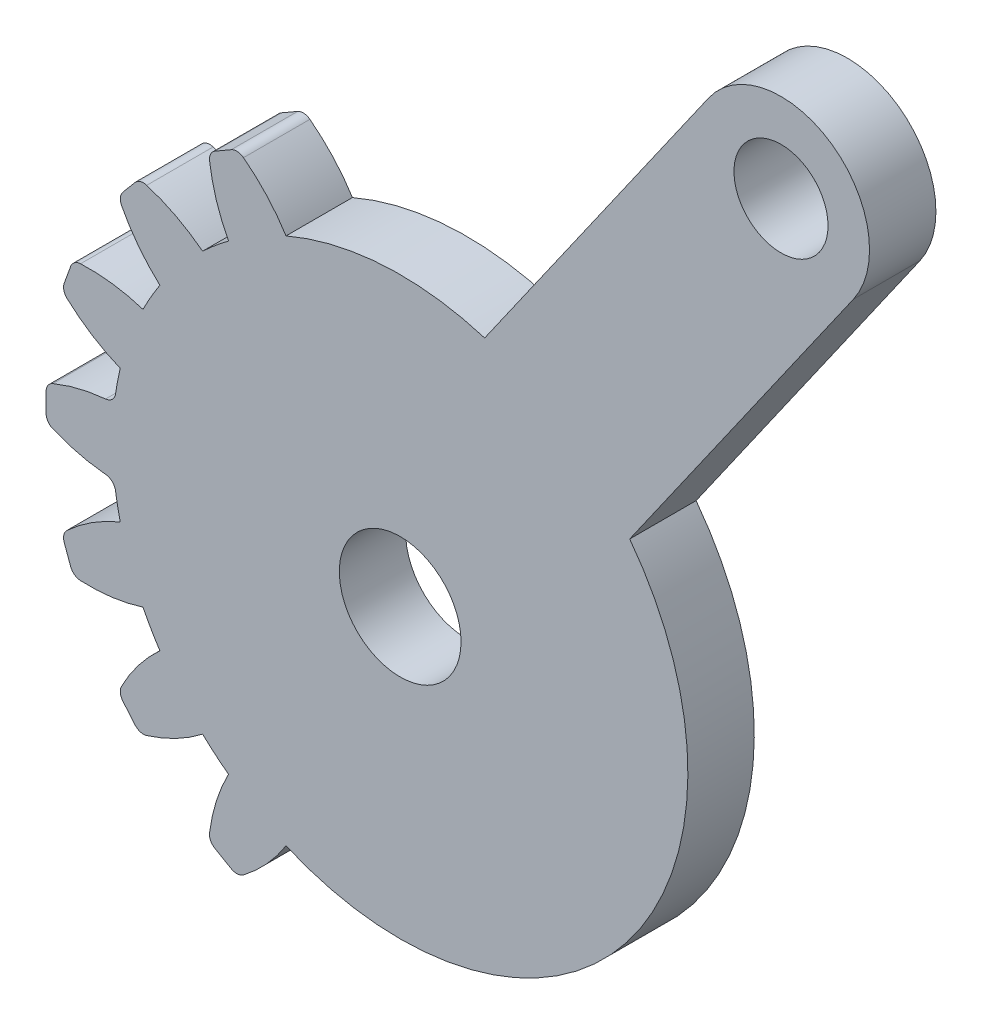
SolidWorks part; units mm, degrees
material "ABS"
ref_plane "Front Plane" through (0, 0, 0) normal (0, 0, 1) x (1, 0, 0)
ref_plane "Top Plane" through (0, 0, 0) normal (0, 1, 0) x (1, 0, 0)
ref_plane "Right Plane" through (0, 0, 0) normal (1, 0, 0) x (0, 0, -1)
sketch "Sketch1" plane through (0, 0, 0) normal (0, 0, 1) x (1, 0, 0)
  circle A1 centre (43.95, -5.65) radius 2.75
  circle A2 centre (43.95, -5.65) radius 13
  dimension "D1" = 26
  dimension "D2" = 5.5
extrude "Boss-Extrude1" add sketch "Sketch1" along normal blind 3 contours A2
sketch "Sketch2" plane through (0, 0, 3) normal (0, 0, 1) x (1, 0, 0)
  line L0 (43.95, -5.65) -> (-22.5318, -5.65) construction
  line L1 (27.95, -4.9) -> (27.95, -6.4)
  arc A0 (27.95, -6.4) -> (31.0368, -7.15) centre (31.3446, 0.8441) ccw
  arc A1 (31.0368, -4.15) -> (31.0368, -7.15) centre (43.95, -5.65) ccw
  circle A2 centre (43.95, -5.65) radius 13 construction
  arc A3 (27.95, -4.9) -> (31.0368, -4.15) centre (31.3446, -12.1441) cw
  point P10 (27.95, -5.65)
  dimension "D3" = 8
  dimension "D1" = 0.75
  dimension "D2" = 1.5
  dimension "D4" = 16
extrude "Boss-Extrude2" add sketch "Sketch2" against normal blind 3
fillet "Fillet1" radius 0.5 4 edges at (31.0368, -7.15, 1.5) (27.95, -6.4, 1.5) (27.95, -4.9, 1.5) (31.0368, -4.15, 1.5)
pattern_circular "CirPattern1" count 4 over 60 about axis through (43.95, -5.65, 0) along (0, 0, 1) of "Boss-Extrude2"
pattern_circular "CirPattern2" count 4 over 60 about axis through (43.95, -5.65, 0) along (0, 0, 1) of "Boss-Extrude2"
sketch "Sketch3" plane through (0, 0, 3) normal (0, 0, 1) x (1, 0, 0)
  line L0 (43.95, -5.65) -> (75.3027, -5.65) construction
  line L1 (43.8, 1.1095) -> (57.8807, 21.2189)
  line L2 (64.4339, 16.6303) -> (49.8678, -4.1723)
  line L3 (61.1573, 18.9246) -> (43.95, -5.65) construction
  line L4 (43.8, 1.1095) -> (49.8678, -4.1723)
  arc A0 (57.8807, 21.2189) -> (64.4339, 16.6303) centre (61.1573, 18.9246) cw
  circle A1 centre (61.1573, 18.9246) radius 2.125
  dimension "D4" = 4.25
  dimension "D1" = 8
  dimension "D2" = 30
  dimension "D3" = 55
  dimension "D5" = 5
extrude "Boss-Extrude3" add sketch "Sketch3" against normal blind 3
fillet "Fillet2" radius 0.5 12 edges at (36.5995, -19.8814, 1.5) (35.3005, -19.1314, 1.5) (32.1754, -16.5091, 1.5) (31.2112, -15.3601, 1.5) (29.1714, -11.8271, 1.5) (28.6584, -10.4176, 1.5) (28.6584, -0.8824, 1.5) (29.1714, 0.5271, 1.5) (31.2112, 4.0601, 1.5) (32.1754, 5.2091, 1.5) (35.3005, 7.8314, 1.5) (36.5995, 8.5814, 1.5)
